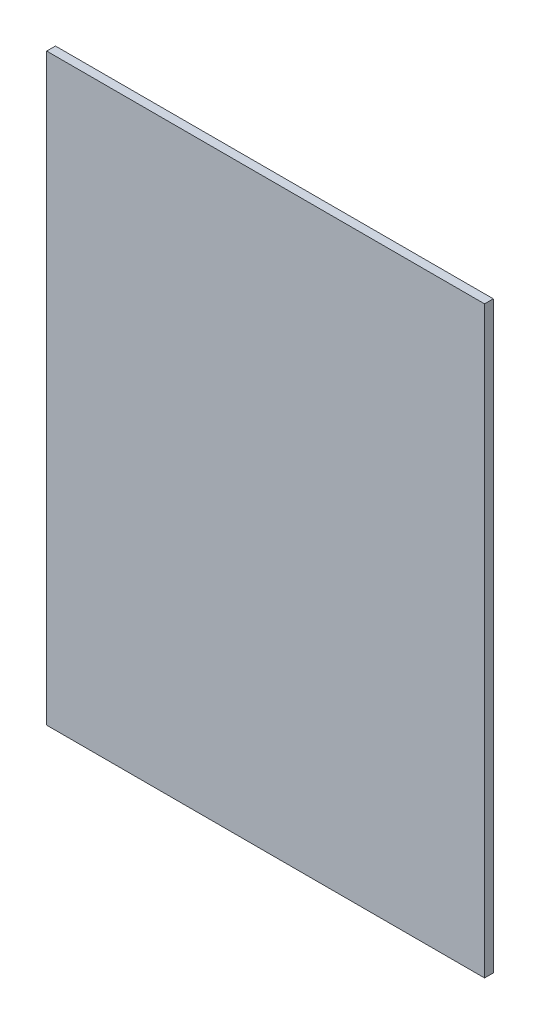
SolidWorks part; units mm, degrees
ref_plane "Plano frontal" through (0, 0, 0) normal (0, 0, 1) x (1, 0, 0)
ref_plane "Plano superior" through (0, 0, 0) normal (0, 1, 0) x (1, 0, 0)
ref_plane "Plano direito" through (0, 0, 0) normal (1, 0, 0) x (0, 0, -1)
sketch "Esboço1" plane through (0, 0, 0) normal (0, 0, 1) x (1, 0, 0)
  line L1 (-75, -100) -> (75, -100)
  line L2 (-75, -100) -> (-75, 100)
  line L3 (-75, 100) -> (75, 100)
  line L4 (75, -100) -> (75, 100)
  line L5 (-75, -100) -> (75, 100) construction
  line L6 (-75, 100) -> (75, -100) construction
  point P0 (0, 0)
  dimension "D1" = 200
  dimension "D2" = 150
extrude "Ressalto-extrusão1" add sketch "Esboço1" along normal blind 3
